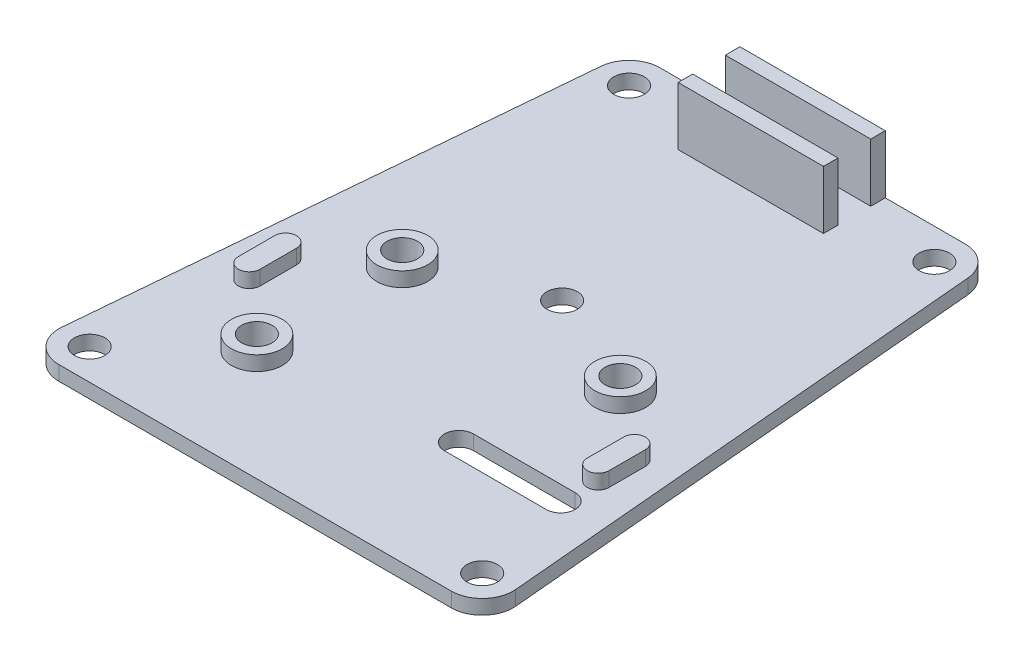
SolidWorks part; units mm, degrees
ref_plane "Alzado" through (0, 0, 0) normal (0, 0, 1) x (1, 0, 0)
ref_plane "Planta" through (0, 0, 0) normal (0, 1, 0) x (1, 0, 0)
ref_plane "Vista lateral" through (0, 0, 0) normal (1, 0, 0) x (0, 0, -1)
sketch "Croquis1" plane through (0, 0, 0) normal (0, 1, 0) x (1, 0, 0)
  line L0 (0, 0) -> (0, -109.7667) construction
  line L1 (-21, 4.25) -> (21, 4.25)
  line L4 (-31.2336, -67.8275) -> (-25.2336, 0.3725)
  line L6 (-27, -72.45) -> (27, -72.45)
  line L14 (31.2336, -67.8275) -> (25.2336, 0.3725)
  line L16 (-37.5, -34.7) -> (-37.5, -59.7) construction
  line L17 (-37.5, -59.7) -> (37.5, -59.7) construction
  line L18 (37.5, -59.7) -> (37.5, -34.7) construction
  line L19 (37.5, -34.7) -> (-37.5, -34.7) construction
  line L20 (-37.5, -34.7) -> (37.5, -59.7) construction
  line L21 (0, -47.2) -> (-26.4653, -47.2) construction
  line L22 (9.8, -54.2) -> (23.8, -54.2) construction
  line L23 (9.8, -52.2) -> (23.8, -52.2)
  line L24 (9.8, -56.2) -> (23.8, -56.2)
  circle A0 centre (-21, 0) radius 2.1
  arc A1 (-21, 4.25) -> (-25.2336, 0.3725) centre (-21, 0) ccw
  circle A4 centre (21, 0) radius 2.1
  circle A5 centre (0, -30.2) radius 2.1
  circle A6 centre (-27, -68.2) radius 2.1
  circle A7 centre (27, -68.2) radius 2.1
  arc A8 (-31.2336, -67.8275) -> (-27, -72.45) centre (-27, -68.2) ccw
  arc A9 (31.2336, -67.8275) -> (27, -72.45) centre (27, -68.2) cw
  arc A10 (21, 4.25) -> (25.2336, 0.3725) centre (21, 0) cw
  circle A11 centre (-15, -37.2) radius 2.1
  circle A12 centre (-15, -57.2) radius 2.1
  circle A13 centre (15, -37.2) radius 2.1
  arc A14 (9.8, -52.2) -> (9.8, -56.2) centre (9.8, -54.2) ccw
  arc A15 (23.8, -56.2) -> (23.8, -52.2) centre (23.8, -54.2) ccw
  point P3 (16.8, -54.2)
  point P9 (0, 4.25)
  point P13 (0, -4)
  point P35 (0, -72.45)
  point P38 (0, -34.7)
  dimension "D1" = 4.2
  dimension "D2" = 8.5
  dimension "D3" = 42
  dimension "D4" = 30.2
  dimension "D5" = 68.2
  dimension "D6" = 54
  dimension "D9" = 15
  dimension "D10" = 10
  dimension "D11" = 17
  dimension "D12" = 4.2
  dimension "D13" = 7
  dimension "D15" = 2
  dimension "D7" = 75
  dimension "D8" = 25
  dimension "D14" = 16.8
  dimension "D16" = 14
extrude "Saliente-Extruir1" add sketch "Croquis1" along normal blind 2
sketch "Croquis2" plane through (0, 2, 0) normal (0, 1, 0) x (1, 0, 0)
  line L0 (21, 4.25) -> (-21, 4.25) construction
  line L1 (-10, -4.25) -> (10, -4.25)
  line L2 (-10, -4.25) -> (-10, 4.25)
  line L3 (-10, 4.25) -> (10, 4.25)
  line L4 (10, -4.25) -> (10, 4.25)
  line L5 (-10, -4.25) -> (10, 4.25) construction
  line L6 (-10, 4.25) -> (10, -4.25) construction
  line L7 (-10, 2.25) -> (10, 2.25)
  line L8 (0, 0) -> (6.77, 0) construction
  line L9 (-10, -2.25) -> (10, -2.25)
  point P0 (0, 0)
  dimension "D1" = 20
  dimension "D2" = 2
extrude "Saliente-Extruir2" add sketch "Croquis2" along normal blind 8
sketch "Croquis3" plane through (0, 2, 0) normal (0, 1, 0) x (1, 0, 0)
  line L0 (24, -44.25) -> (24, -49.25) construction
  line L1 (25.5, -44.25) -> (25.5, -49.25)
  line L2 (22.5, -44.25) -> (22.5, -49.25)
  line L3 (21, 4.25) -> (10, 4.25) construction
  line L4 (0, 0) -> (0, -88.846) construction
  line L5 (-24, -44.25) -> (-24, -49.25) construction
  line L6 (-25.5, -44.25) -> (-25.5, -49.25)
  line L7 (-22.5, -44.25) -> (-22.5, -49.25)
  circle A0 centre (-15, -37.2) radius 3.5
  circle A1 centre (-15, -57.2) radius 3.5
  circle A2 centre (15, -37.2) radius 3.5
  circle A3 centre (-15, -57.2) radius 2.1 construction
  circle A4 centre (-15, -37.2) radius 2.1 construction
  circle A5 centre (-15, -57.2) radius 2.1
  circle A6 centre (-15, -37.2) radius 2.1
  arc A7 (25.5, -44.25) -> (22.5, -44.25) centre (24, -44.25) ccw
  arc A8 (22.5, -49.25) -> (25.5, -49.25) centre (24, -49.25) ccw
  arc A9 (-25.5, -44.25) -> (-22.5, -44.25) centre (-24, -44.25) cw
  arc A10 (-22.5, -49.25) -> (-25.5, -49.25) centre (-24, -49.25) cw
  point P17 (24, -46.75)
  point P29 (-24, -46.75)
  circle M5 centre (-15, -57.2) radius 2.1
  circle M17 centre (-15, -37.2) radius 2.1
  circle M18 centre (15, -37.2) radius 2.1
  dimension "D1" = 7
  dimension "D3" = 1.5
  dimension "D2" = 51
  dimension "D4" = 24
  dimension "D5" = 5
extrude "Saliente-Extruir3" add sketch "Croquis3" along normal blind 2 contours A2 M18 | A0 M17 | A1 M5 | L6 A10 L7 A9 | L2 A8 L1 A7
